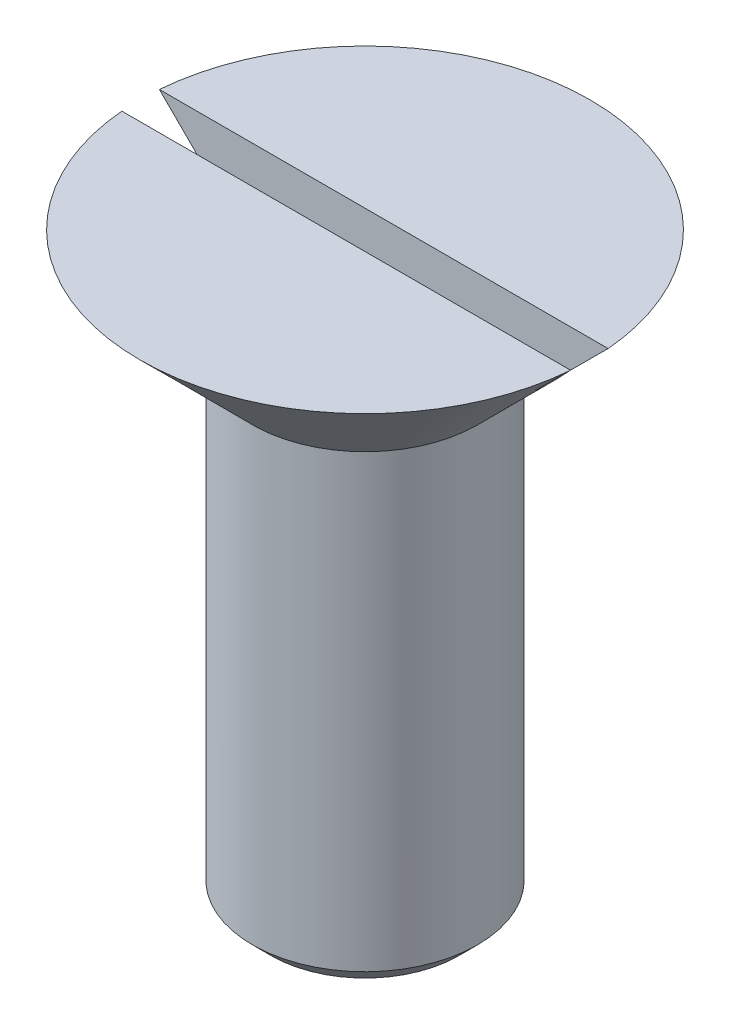
SolidWorks part; units mm, degrees
ref_plane "Front Plane" through (0, 0, 0) normal (0, 0, 1) x (1, 0, 0)
ref_plane "Top Plane" through (0, 0, 0) normal (0, 1, 0) x (1, 0, 0)
ref_plane "Right Plane" through (0, 0, 0) normal (1, 0, 0) x (0, 0, -1)
sketch "Sketch2" plane through (0, 0, 0) normal (0, 0, 1) x (1, 0, 0)
  line L0 (0, 34.8479) -> (0, 0) construction
  line L1 (1, 31) -> (1, 29)
  line L2 (1, 29) -> (0, 29)
  line L3 (1, 31) -> (12, 31)
  line L4 (12, 31) -> (6, 25)
  line L5 (6, 25) -> (6, 0)
  line L6 (6, 0) -> (0, 0)
  line L7 (0, 0) -> (0, 29)
  point P10 (0, 0)
  point P11 (0, 0)
  dimension "D1" = 45
  dimension "D2" = 6
  dimension "D3" = 2
  dimension "D4" = 1
  dimension "D5" = 6
  dimension "D6" = 25
revolve "Revolve1" add sketch "Sketch2" angle 360 about L7
sketch "Sketch3" plane through (0, 0, 0) normal (1, 0, 0) x (0, 0, -1)
  line L0 (1, 31) -> (-1, 31) construction
  line L1 (-1, 31) -> (1, 31)
  line L2 (-1, 31) -> (-1, 29)
  line L3 (-1, 29) -> (1, 29)
  line L4 (1, 31) -> (1, 29)
  point P6 (0, 29)
  dimension "D1" = 2
  dimension "D2" = 2
extrude "Cut-Extrude1" cut sketch "Sketch3" against normal through all both and the other way through all contours L2 L1 L4 L3
chamfer "Chamfer1" distance 1 angle 45 1 edges at (6, 0, 0)
